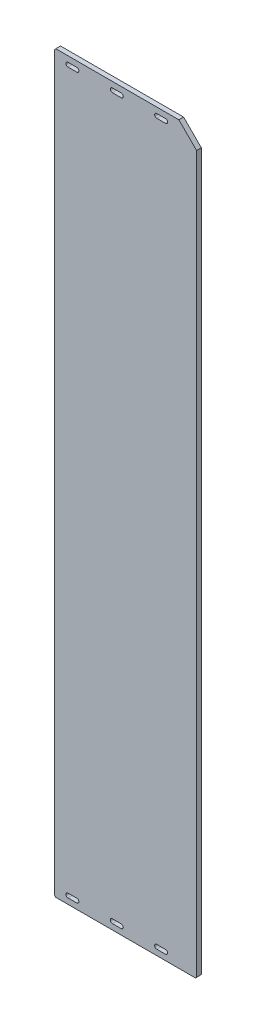
SolidWorks part; units mm, degrees
ref_plane "前视基准面" through (0, 0, 0) normal (0, 0, 1) x (1, 0, 0)
ref_plane "上视基准面" through (0, 0, 0) normal (0, 1, 0) x (1, 0, 0)
ref_plane "右视基准面" through (0, 0, 0) normal (1, 0, 0) x (0, 0, -1)
sketch "草图1" plane through (0, 0, 0) normal (0, 0, 1) x (1, 0, 0)
  line L1 (-120, -621) -> (120, -621)
  line L2 (-120, -621) -> (-120, 621)
  line L3 (-120, 621) -> (120, 621)
  line L4 (120, -621) -> (120, 621)
  line L5 (-120, -621) -> (120, 621) construction
  line L6 (-120, 621) -> (120, -621) construction
  point P0 (0, 0)
  dimension "D1" = 240
  dimension "D2" = 1242
extrude "凸台-拉伸1" add sketch "草图1" along normal blind 8
chamfer "倒角1" distance 30 angle 45 1 edges at (120, 621, 4)
chamfer "倒角2" distance 2 angle 45 3 edges at (120, -621, 4) (-120, -621, 4) (-120, 621, 4)
sketch "草图2" plane through (0, 0, 0) normal (0, 0, -1) x (-1, 0, 0)
  line L0 (-67.5, 608) -> (-52.5, 608) construction
  line L1 (-67.5, 611.5) -> (-52.5, 611.5)
  line L2 (-67.5, 604.5) -> (-52.5, 604.5)
  line L3 (7.5, 608) -> (22.5, 608) construction
  line L4 (7.5, 611.5) -> (22.5, 611.5)
  line L5 (7.5, 604.5) -> (22.5, 604.5)
  line L6 (82.5, 608) -> (97.5, 608) construction
  line L7 (82.5, 611.5) -> (97.5, 611.5)
  line L8 (82.5, 604.5) -> (97.5, 604.5)
  line L9 (0, 0) -> (120, 0) construction
  line L10 (120, 619) -> (120, -619) construction
  line L11 (-67.5, -608) -> (-52.5, -608) construction
  line L12 (-67.5, -611.5) -> (-52.5, -611.5)
  line L13 (-67.5, -604.5) -> (-52.5, -604.5)
  line L14 (7.5, -608) -> (22.5, -608) construction
  line L15 (7.5, -611.5) -> (22.5, -611.5)
  line L16 (7.5, -604.5) -> (22.5, -604.5)
  line L17 (82.5, -608) -> (97.5, -608) construction
  line L18 (82.5, -611.5) -> (97.5, -611.5)
  line L19 (82.5, -604.5) -> (97.5, -604.5)
  arc A0 (-67.5, 611.5) -> (-67.5, 604.5) centre (-67.5, 608) ccw
  arc A1 (-52.5, 604.5) -> (-52.5, 611.5) centre (-52.5, 608) ccw
  arc A2 (7.5, 611.5) -> (7.5, 604.5) centre (7.5, 608) ccw
  arc A3 (22.5, 604.5) -> (22.5, 611.5) centre (22.5, 608) ccw
  arc A4 (82.5, 611.5) -> (82.5, 604.5) centre (82.5, 608) ccw
  arc A5 (97.5, 604.5) -> (97.5, 611.5) centre (97.5, 608) ccw
  arc A6 (-67.5, -611.5) -> (-67.5, -604.5) centre (-67.5, -608) cw
  arc A7 (-52.5, -604.5) -> (-52.5, -611.5) centre (-52.5, -608) cw
  arc A8 (7.5, -611.5) -> (7.5, -604.5) centre (7.5, -608) cw
  arc A9 (22.5, -604.5) -> (22.5, -611.5) centre (22.5, -608) cw
  arc A10 (82.5, -611.5) -> (82.5, -604.5) centre (82.5, -608) cw
  arc A11 (97.5, -604.5) -> (97.5, -611.5) centre (97.5, -608) cw
  point P2 (-60, 608)
  point P9 (15, 608)
  point P17 (90, 608)
  point P32 (-60, -608)
  point P39 (15, -608)
  point P46 (90, -608)
  dimension "D1" = 3.5
  dimension "D2" = 15
extrude "切除-拉伸1" cut sketch "草图2" against normal blind 10
